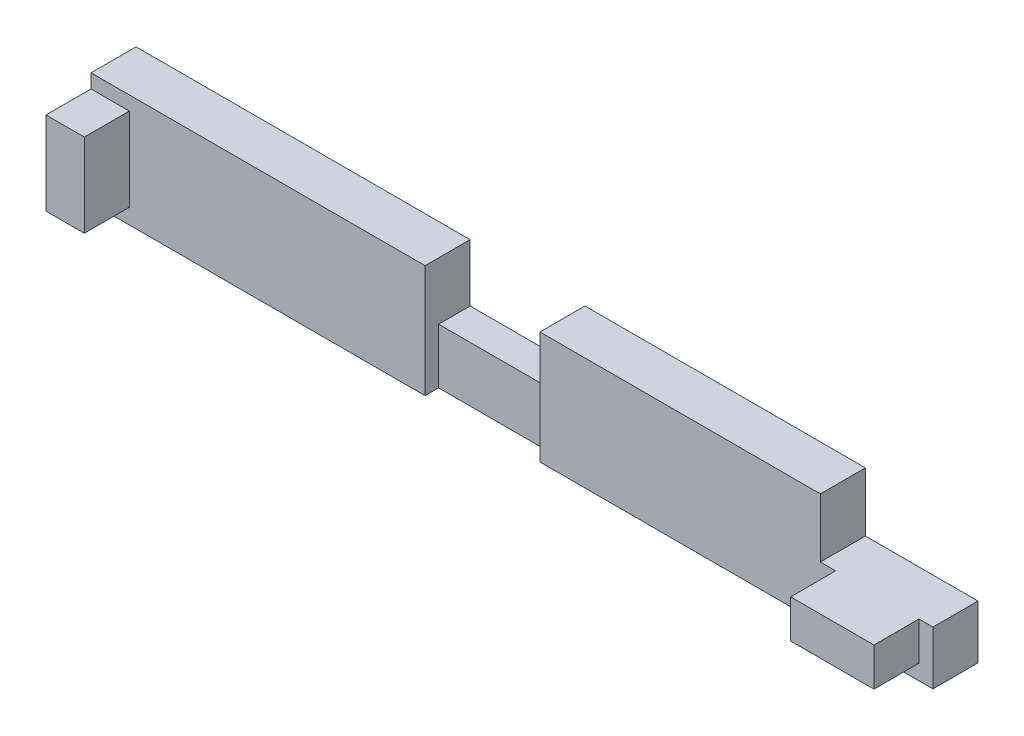
SolidWorks part; units mm, degrees
ref_plane "Front Plane" through (0, 0, 0) normal (0, 0, 1) x (1, 0, 0)
ref_plane "Top Plane" through (0, 0, 0) normal (0, 1, 0) x (1, 0, 0)
ref_plane "Right Plane" through (0, 0, 0) normal (1, 0, 0) x (0, 0, -1)
sketch "Sketch1" plane through (0, 0, 0) normal (0, 0, 1) x (1, 0, 0)
  line L1 (0, 0) -> (200, 0)
  line L2 (0, 0) -> (0, 25)
  line L3 (0, 25) -> (200, 25)
  line L4 (200, 0) -> (200, 25)
  dimension "D1" = 200
  dimension "D2" = 25
extrude "Boss-Extrude1" add sketch "Sketch1" along normal blind 10
sketch "Sketch2" plane through (0, 0, 10) normal (0, 0, 1) x (1, 0, 0)
  line L0 (200, 25) -> (0, 25) construction
  line L1 (196.9, 21.9) -> (178.4, 21.9)
  line L2 (196.9, 21.9) -> (196.9, 3.4)
  line L3 (196.9, 3.4) -> (178.4, 3.4)
  line L4 (178.4, 21.9) -> (178.4, 3.4)
  line L5 (200, 0) -> (200, 25) construction
  line L6 (177.95, 11.9) -> (196.9, 11.9)
  line L7 (0, 25) -> (0, 0) construction
  line L8 (3.1, 21.9) -> (21.6, 21.9)
  line L9 (3.1, 21.9) -> (3.1, 3.4)
  line L10 (3.1, 3.4) -> (21.6, 3.4)
  line L11 (21.6, 21.9) -> (21.6, 3.4)
  line L12 (13.1, 21.9) -> (13.1, 3.4)
  point P18 (0, 0)
  point P20 (12.6, 3.4)
  dimension "D1" = 3.1
  dimension "D2" = 3.1
  dimension "D3" = 18.5
  dimension "D4" = 18.5
  dimension "D5" = 18.5
  dimension "D6" = 18.5
  dimension "D7" = 3.1
  dimension "D8" = 3.1
  dimension "D9" = 8.5
  dimension "D10" = 8.5
sketch "Sketch3" plane through (0, 0, 10) normal (0, 0, 1) x (1, 0, 0)
  line L0 (0, 0) -> (200, 0) construction
  line L1 (0, 25) -> (13.1, 25)
  line L2 (0, 25) -> (0, 0)
  line L3 (0, 0) -> (13.1, 0)
  line L4 (13.1, 25) -> (13.1, 0)
  line L8 (200, 11.9) -> (175, 11.9)
  line L10 (200, 25) -> (175, 25)
  line L11 (200, 25) -> (200, 11.9)
  line L12 (200, 11.9) -> (175, 11.9)
  line L13 (175, 25) -> (175, 11.9)
  line M3 (0, 25) -> (0, 0)
  line M4 (0, 0) -> (200, 0)
  line M5 (200, 0) -> (200, 25)
  line M6 (200, 25) -> (0, 25)
  dimension "D1" = 25
  dimension "D2" = 13.1
  dimension "D3" = 13.1
sketch "Sketch4" plane through (0, 0, 10) normal (0, 0, 1) x (1, 0, 0)
  line L0 (0, 0) -> (200, 0) construction
  line L9 (200, 0) -> (200, 25) construction
  line L10 (87.25, 37.75) -> (112.75, 37.75)
  line L11 (87.25, 37.75) -> (87.25, 12.25)
  line L12 (87.25, 12.25) -> (112.75, 12.25)
  line L13 (112.75, 37.75) -> (112.75, 12.25)
  line L14 (87.25, 37.75) -> (112.75, 12.25) construction
  line L15 (87.25, 12.25) -> (112.75, 37.75) construction
  point P0 (100, 25)
  dimension "D1" = 25.5
  dimension "D2" = 100
  dimension "D3" = 25
extrude "Cut-Extrude2" cut sketch "Sketch4" against normal blind 10
extrude "Boss-Extrude3" add sketch "Sketch2" along normal blind 10 contours L6 L4 L3 L2 | L8 L12 L10 L11
extrude "Cut-Extrude3" cut sketch "Sketch3" against normal blind 10 contours L4 M6 M3 M4 | L13 L8 M6 M5
sketch "Sketch5" plane through (0, 12.25, 0) normal (0, 1, 0) x (1, 0, 0)
  line L0 (112.75, 0) -> (112.75, -10) construction
  line L1 (87.25, -10) -> (112.75, -10)
  line L2 (87.25, -10) -> (87.25, -7)
  line L3 (87.25, -7) -> (112.75, -7)
  line L4 (112.75, -10) -> (112.75, -7)
  dimension "D1" = 3
extrude "Cut-Extrude4" cut sketch "Sketch5" against normal blind 13
